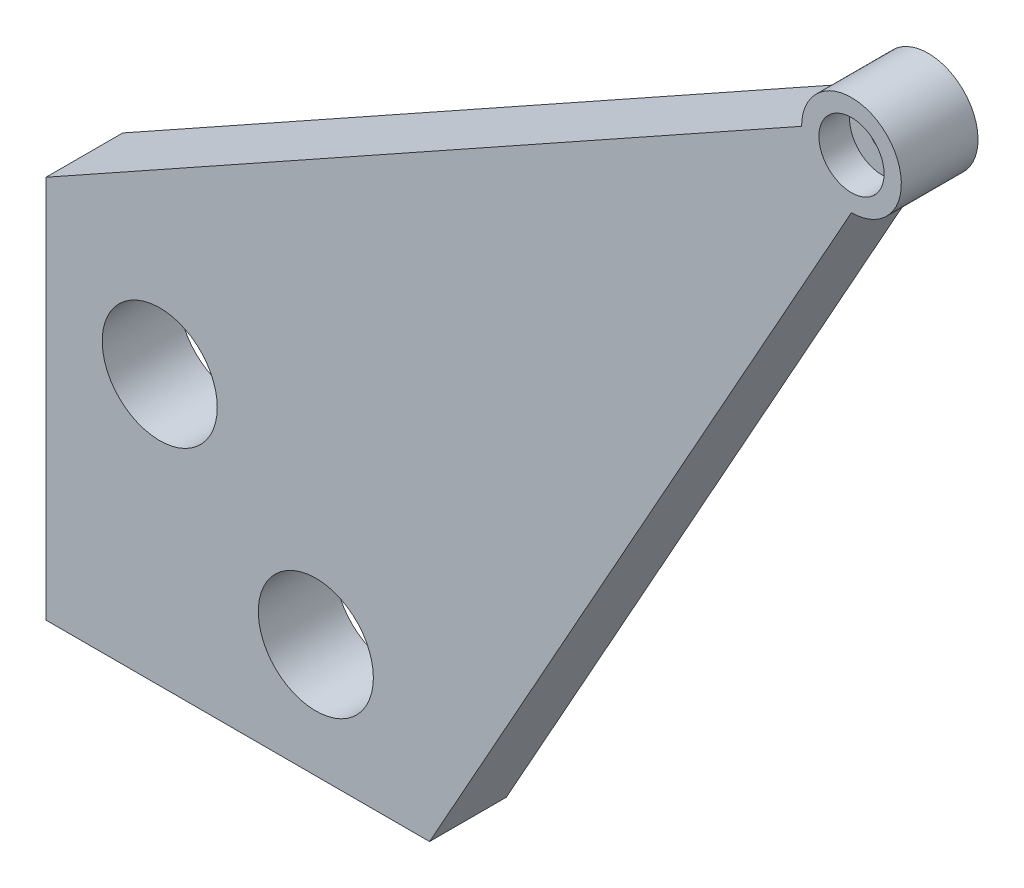
SolidWorks part; units mm, degrees
ref_plane "Plano frontal" through (0, 0, 0) normal (0, 0, 1) x (1, 0, 0)
ref_plane "Plano superior" through (0, 0, 0) normal (0, 1, 0) x (1, 0, 0)
ref_plane "Plano direito" through (0, 0, 0) normal (1, 0, 0) x (0, 0, -1)
sketch "Esboço3" plane through (0, 0, 0) normal (0, 0, 1) x (1, 0, 0)
  line L0 (-62.966, 0) -> (106.6858, 0) construction
  line L1 (0, 69.7378) -> (0, -73.302) construction
  line L2 (0, 50) -> (98.5, 105)
  line L3 (0, 0) -> (50, 0)
  line L4 (0, 0) -> (0, 50)
  line L7 (50, 0) -> (105, 98.5)
  arc A0 (105, 98.5) -> (98.5, 105) centre (105, 105) ccw
  dimension "D4" = 105
  dimension "D5" = 13
  dimension "D3" = 105
extrude "Ressalto-extrusão2" add sketch "Esboço3" along normal mid plane 10
sketch "Esboço4" plane through (0, 0, 5) normal (0, 0, 1) x (1, 0, 0)
  circle A0 centre (105, 105) radius 4.25
  arc A1 (105, 98.5) -> (98.5, 105) centre (105, 105) ccw construction
  dimension "D1" = 8.5
extrude "Corte-extrusão1" cut sketch "Esboço4" against normal blind 4 contours A0
sketch "Esboço5" plane through (0, 0, 1) normal (0, 0, 1) x (1, 0, 0)
  circle A0 centre (105, 105) radius 1.5
  circle A1 centre (105, 105) radius 4.25 construction
extrude "Corte-extrusão2" cut sketch "Esboço5" against normal through all
sketch "Esboço6" plane through (0, 0, 5) normal (0, 0, 1) x (1, 0, 0)
  line L0 (-26.6702, 0) -> (72.5742, 0) construction
  line L1 (0, 62.2144) -> (0, -11.4301) construction
  line L2 (0, 50) -> (63.2897, 50) construction
  line L3 (50, 0) -> (50, 50) construction
  line L4 (0, 50) -> (14.8256, 35.1744) construction
  line L5 (14.8256, 35.1744) -> (35.1744, 14.8256) construction
  line L6 (35.1744, 14.8256) -> (50, 0) construction
  line L7 (0, 0) -> (50, 50) construction
  circle A0 centre (14.8256, 35.1744) radius 7.5
  circle A1 centre (35.1744, 14.8256) radius 7.5
  point P16 (0, 0)
  dimension "D1" = 15
  dimension "D2" = 15
extrude "Corte-extrusão3" cut sketch "Esboço6" against normal through all
